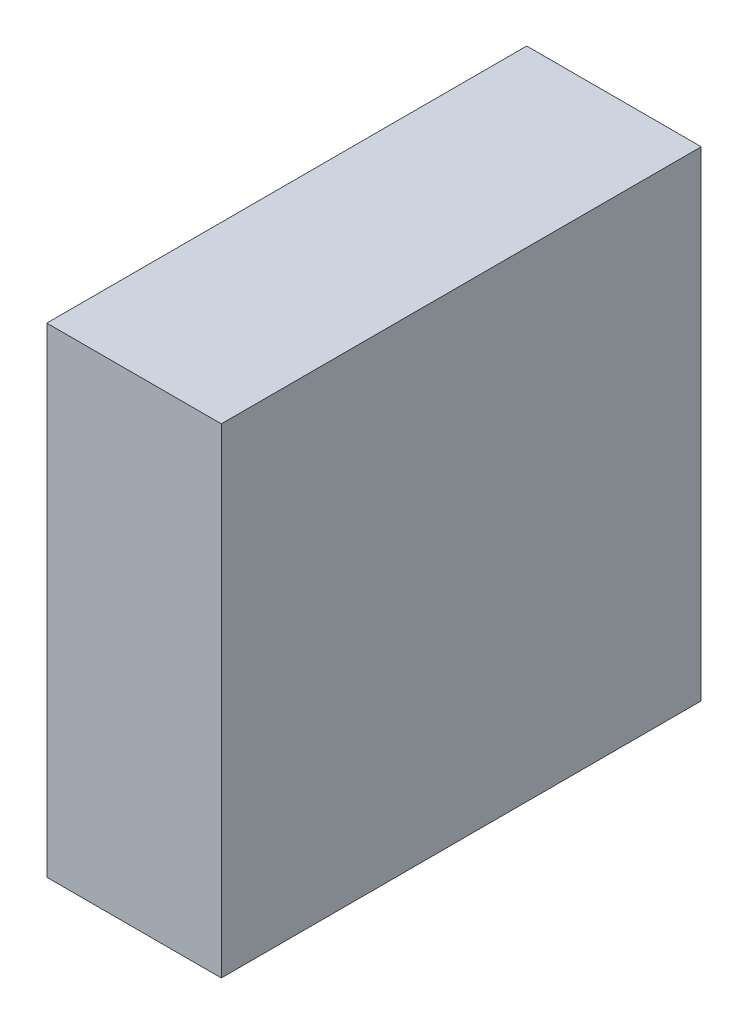
SolidWorks part; units mm, degrees
material "山毛榉"
ref_plane "前视基准面" through (0, 0, 0) normal (0, 0, 1) x (1, 0, 0)
ref_plane "上视基准面" through (0, 0, 0) normal (0, 1, 0) x (1, 0, 0)
ref_plane "右视基准面" through (0, 0, 0) normal (1, 0, 0) x (0, 0, -1)
sketch "草图1" plane through (0, 0, 0) normal (1, 0, 0) x (0, 0, -1)
  line L5 (56.0822, 53.2) -> (-53.9178, 53.2)
  line L6 (56.0822, 53.2) -> (56.0822, -56.8)
  line L7 (56.0822, -56.8) -> (-53.9178, -56.8)
  line L8 (-53.9178, 53.2) -> (-53.9178, -56.8)
  dimension "D1" = 110
  dimension "D2" = 110
extrude "凸台-拉伸2" add sketch "草图1" along normal blind 40
